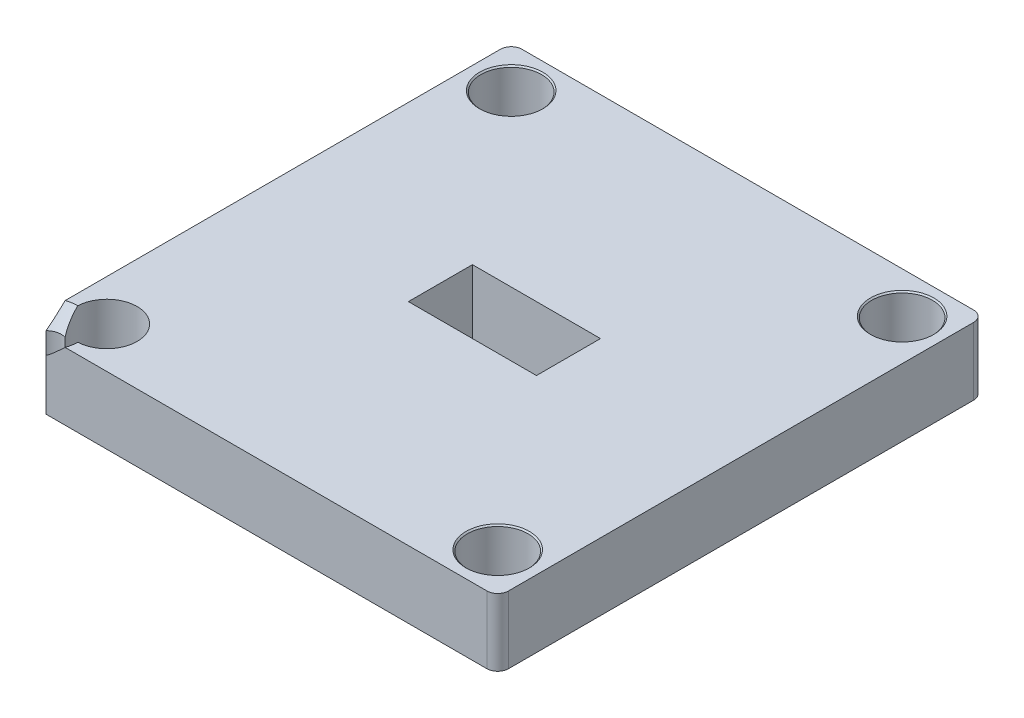
SolidWorks part; units mm, degrees
ref_plane "Спереди" through (0, 0, 0) normal (0, 0, 1) x (1, 0, 0)
ref_plane "Сверху" through (0, 0, 0) normal (0, 1, 0) x (1, 0, 0)
ref_plane "Справа" through (0, 0, 0) normal (1, 0, 0) x (0, 0, -1)
sketch "Эскиз2" plane through (0, 0, 0) normal (0, 1, 0) x (1, 0, 0)
  line L1 (-9.5, -4.75) -> (9.5, -4.75)
  line L2 (-9.5, -4.75) -> (-9.5, 4.75)
  line L3 (-9.5, 4.75) -> (9.5, 4.75)
  line L4 (9.5, -4.75) -> (9.5, 4.75)
  line L5 (-9.5, -4.75) -> (9.5, 4.75) construction
  line L6 (-9.5, 4.75) -> (9.5, -4.75) construction
  line L17 (33.5, -36.1) -> (-33.5, -36.1)
  line L18 (35.1, -34.5) -> (35.1, 34.5)
  line L19 (33.5, 36.1) -> (-33.5, 36.1)
  line L20 (-35.1, -34.5) -> (-35.1, 34.5)
  line L21 (35.1, -36.1) -> (-35.1, 36.1) construction
  line L22 (35.1, 36.1) -> (-35.1, -36.1) construction
  circle A0 centre (-29, 30) radius 4.5
  circle A1 centre (29, 30) radius 4.5
  circle A2 centre (29, -30) radius 4.5
  circle A3 centre (-29, -30) radius 4.5
  arc A4 (-35.1, 34.5) -> (-33.5, 36.1) centre (-33.5, 34.5) cw
  arc A5 (33.5, -36.1) -> (35.1, -34.5) centre (33.5, -34.5) ccw
  arc A6 (-33.5, -36.1) -> (-35.1, -34.5) centre (-33.5, -34.5) cw
  arc A7 (35.1, 34.5) -> (33.5, 36.1) centre (33.5, 34.5) ccw
  point P0 (0, 0)
  point P8 (0, 0)
  point P14 (0, 0)
  point P32 (0, 0)
  dimension "D3" = 2
  dimension "D5" = 1.6
  dimension "D6" = 1.6
  dimension "D1" = 19
  dimension "D2" = 9.5
  dimension "D4" = 2
extrude "Бобышка-Вытянуть1" add sketch "Эскиз2" along normal blind 10
hole_wizard "Зенковка для винта с полупотайной головкой M41" positions "Эскиз3" profile "Эскиз4" countersink size "M4" standard "ISO" end condition through all
sketch "Эскиз3" plane through (0, 10, 0) normal (0, 1, 0) x (1, 0, 0)
  point P0 (-29, 30)
  point P3 (29, 30)
  point P6 (-33.5, -34.5)
  point P9 (29, -30)
sketch "Эскиз4" plane through (-29, 10, -30) normal (1, 0, 0) x (0, 0, 1)
  line L0 (0, 0) -> (0, 10)
  line L1 (0, 10) -> (2.25, 10)
  line L2 (2.25, 10) -> (2.25, 2.45)
  line L3 (2.25, 2.45) -> (4.7, 0)
  line L5 (4.7, 0) -> (0, 0)
  line L6 (-2.25, 2.45) -> (-4.7, 0) construction
  line L11 (0, -6.35) -> (0, 107.95) construction
  dimension "Диаметр сквозного отверстия" = 4.5
  dimension "Глубина сквозного отверстия" = 10
  dimension "Диаметр передней зенковки" = 9.4
  dimension "Угол передней зенковки" = 90
